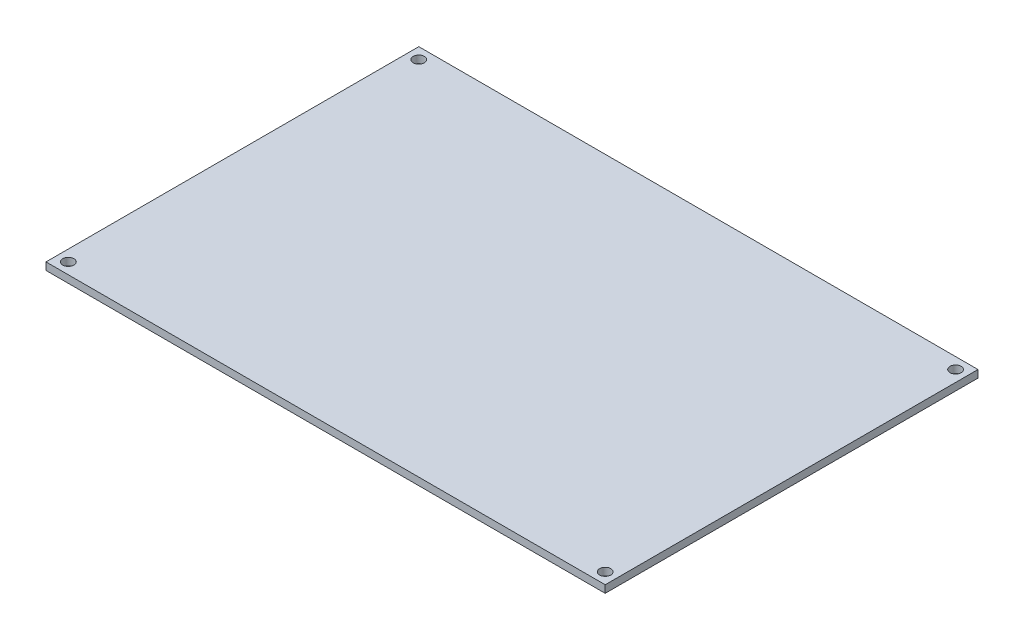
SolidWorks part; units mm, degrees
ref_plane "Front Plane" through (0, 0, 0) normal (0, 0, 1) x (1, 0, 0)
ref_plane "Top Plane" through (0, 0, 0) normal (0, 1, 0) x (1, 0, 0)
ref_plane "Right Plane" through (0, 0, 0) normal (1, 0, 0) x (0, 0, -1)
sketch "Sketch1" plane through (0, 0, 0) normal (0, 1, 0) x (1, 0, 0)
  line L1 (-75, 50) -> (75, 50)
  line L2 (-75, 50) -> (-75, -50)
  line L3 (-75, -50) -> (75, -50)
  line L4 (75, 50) -> (75, -50)
  line L5 (-75, 50) -> (75, -50) construction
  line L6 (-75, -50) -> (75, 50) construction
  point P0 (0, 0)
  dimension "D1" = 100
  dimension "D2" = 150
extrude "Boss-Extrude1" add sketch "Sketch1" along normal blind 2
sketch "Sketch2" plane through (0, 2, 0) normal (0, 1, 0) x (1, 0, 0)
  line L0 (-75, 50) -> (-75, -50) construction
  line L1 (75, 50) -> (-75, 50) construction
  line L2 (-75, -50) -> (75, -50) construction
  line L3 (75, -50) -> (75, 50) construction
  circle A0 centre (-72, 47) radius 1.5
  circle A1 centre (-72, -47) radius 1.5
  circle A2 centre (72, -47) radius 1.5
  circle A3 centre (72, 47) radius 1.5
  point P18 (73.0782, -50)
  dimension "D1" = 3
  dimension "D2" = 3
  dimension "D3" = 3
  dimension "D4" = 3
  dimension "D5" = 3
  dimension "D6" = 3
  dimension "D7" = 3
  dimension "D8" = 3
  dimension "D9" = 3
  dimension "D10" = 3
  dimension "D11" = 3
  dimension "D12" = 3
extrude "Cut-Extrude1" cut sketch "Sketch2" against normal through all
